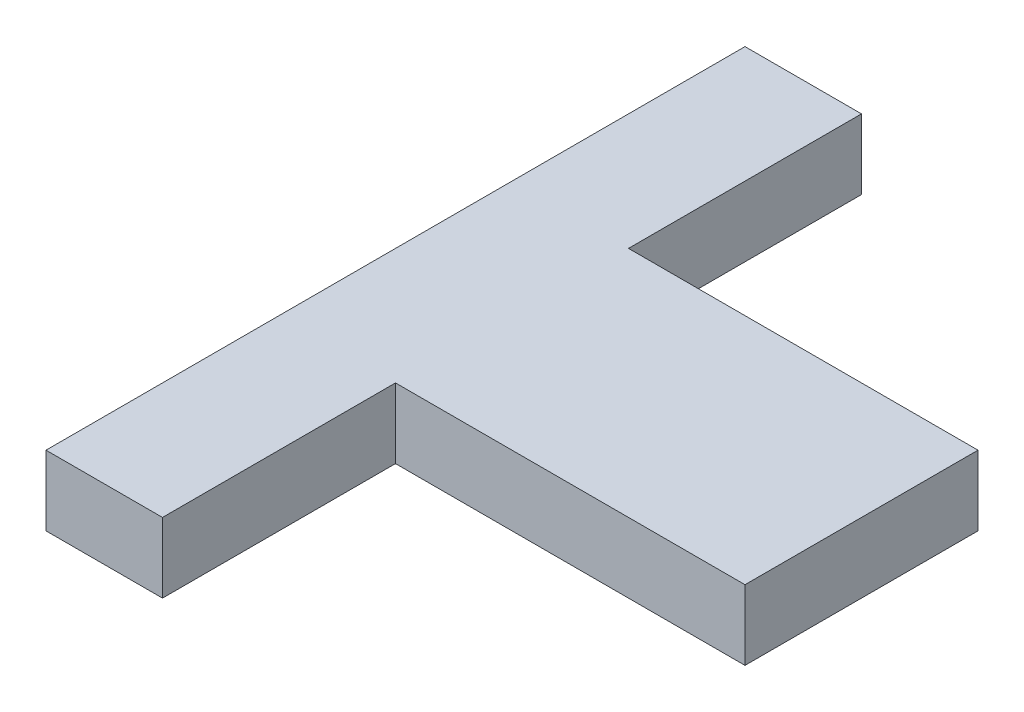
SolidWorks part; units mm, degrees
ref_plane "Front" through (0, 0, 0) normal (0, 0, 1) x (1, 0, 0)
ref_plane "Top" through (0, 0, 0) normal (0, 1, 0) x (1, 0, 0)
ref_plane "Right" through (0, 0, 0) normal (1, 0, 0) x (0, 0, -1)
sketch "Sketch1" plane through (0, 0, 0) normal (0, 1, 0) x (1, 0, 0)
  line L1 (0, 0) -> (10, 0)
  line L2 (0, 0) -> (0, -60)
  line L3 (0, -60) -> (10, -60)
  line L4 (10, 0) -> (10, -60)
  line L5 (10, -20) -> (40, -20)
  line L6 (10, -20) -> (10, -40)
  line L7 (10, -40) -> (40, -40)
  line L8 (40, -20) -> (40, -40)
  point P9 (10, -30)
  dimension "D1" = 10
  dimension "D2" = 60
  dimension "D3" = 20
  dimension "D4" = 10
  dimension "D5" = 30
extrude "Boss-Extrude1" add sketch "Sketch1" along normal blind 6 contours L4 L1 L2 L3 | L8 L5 L4 L7
